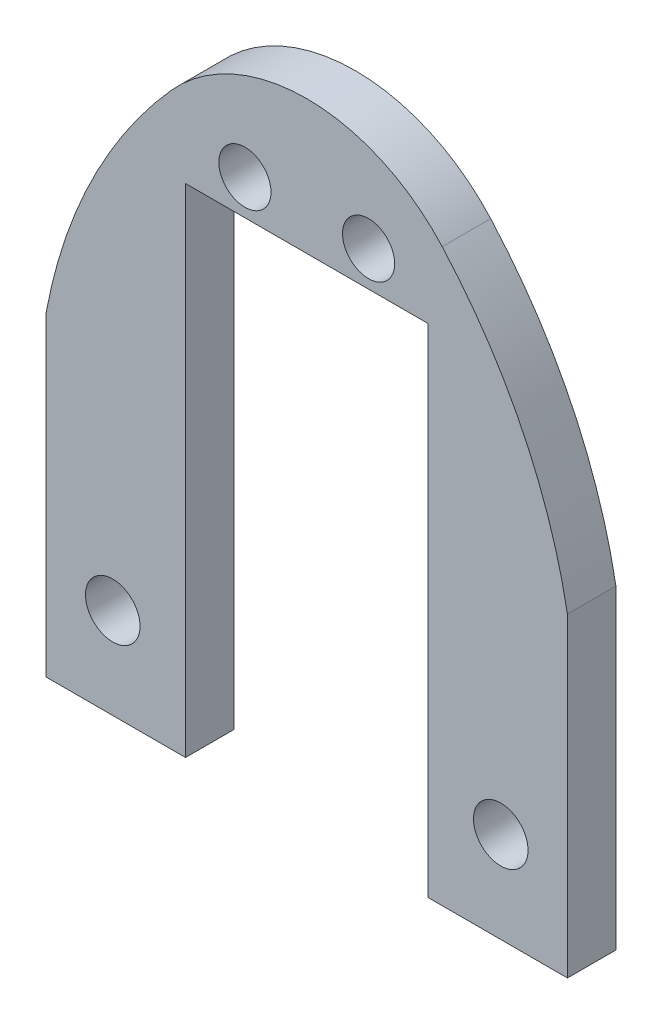
SolidWorks part; units mm, degrees
ref_plane "Plan de face" through (0, 0, 0) normal (0, 0, 1) x (1, 0, 0)
ref_plane "Plan de dessus" through (0, 0, 0) normal (0, 1, 0) x (1, 0, 0)
ref_plane "Plan de droite" through (0, 0, 0) normal (1, 0, 0) x (0, 0, -1)
sketch "Esquisse1" plane through (0, 0, 0) normal (0, 0, 1) x (1, 0, 0)
  line L0 (0, 0) -> (0, 41)
  line L1 (-15, 56) -> (-28, 56)
  line L2 (-43, 41) -> (-43, 0)
  line L3 (-43, 0) -> (-31.5, 0)
  line L4 (-31.5, 0) -> (-31.5, 41)
  line L5 (-31.5, 41) -> (-11.5, 41)
  line L6 (-11.5, 41) -> (-11.5, 0)
  line L7 (-11.5, 0) -> (0, 0)
  line L8 (0, 41) -> (-15, 56)
  line L9 (-28, 56) -> (-43, 41)
  arc A2 (-27.9, 45.6125) -> (-25.3, 45.6125) centre (-26.6, 43.9) ccw construction
  arc A4 (-17.7, 45.6125) -> (-15.1, 45.6125) centre (-16.4, 43.9) ccw construction
  circle A6 centre (-16.4, 43.9) radius 2.15
  circle A7 centre (-26.6, 43.9) radius 2.15
  dimension "D9" = 4.3
  dimension "D10" = 4.3
  dimension "D1" = 11.5
  dimension "D2" = 41
  dimension "D3" = 20
  dimension "D4" = 15
  dimension "D5" = 135
  dimension "D6" = 135
  dimension "D7" = 41
  dimension "D8" = 41
  dimension "D11" = 0
  dimension "D12" = 0
extrude "Boss.-Extru.1" add sketch "Esquisse1" along normal blind 4
sketch "Esquisse2" plane through (0, 0, 4) normal (0, 0, 1) x (1, 0, 0)
  line L0 (-43, 41) -> (-43, 0) construction
  line L1 (-15, 56) -> (-28, 56) construction
  line L2 (-21.5, 56) -> (-21.5, 10.0639) construction
  line L3 (0, 26) -> (0, 41)
  line L4 (0, 41) -> (-15, 56)
  line L5 (-15, 56) -> (-28, 56)
  line L6 (-28, 56) -> (-43, 41)
  line L7 (-43, 41) -> (-43, 26)
  arc A0 (-43, 26) -> (-32.6722, 47.0738) centre (-0.4713, 18.2253) cw
  arc A1 (0, 26) -> (-10.3278, 47.0738) centre (-42.5287, 18.2253) ccw
  arc A2 (-32.6722, 47.0738) -> (-10.3278, 47.0738) centre (-21.5, 37.0647) cw
  dimension "D1" = 15
  dimension "D2" = 15
extrude "Enlèv. mat.-Extru.1" cut sketch "Esquisse2" against normal through all
sketch "Esquisse3" plane through (0, 0, 0) normal (0, 0, -1) x (-1, 0, 0)
  line L0 (21.5, 52.0647) -> (21.5, 11.5993) construction
  arc A0 (35.4037, 6.6826) -> (39.5963, 6.6826) centre (37.5, 7.5) ccw construction
  arc A1 (39.5963, 6.6826) -> (35.4037, 6.6826) centre (37.5, 7.5) ccw construction
  arc A2 (35.4037, 6.6826) -> (39.5963, 6.6826) centre (37.5, 7.5) ccw
  arc A3 (39.5963, 6.6826) -> (35.4037, 6.6826) centre (37.5, 7.5) ccw
  arc A4 (32.6722, 47.0738) -> (10.3278, 47.0738) centre (21.5, 37.0647) ccw construction
  arc A5 (7.5963, 6.6826) -> (3.4037, 6.6826) centre (5.5, 7.5) cw
  arc A6 (3.4037, 6.6826) -> (7.5963, 6.6826) centre (5.5, 7.5) cw
extrude "Enlèv. mat.-Extru.2" cut sketch "Esquisse3" against normal through all
